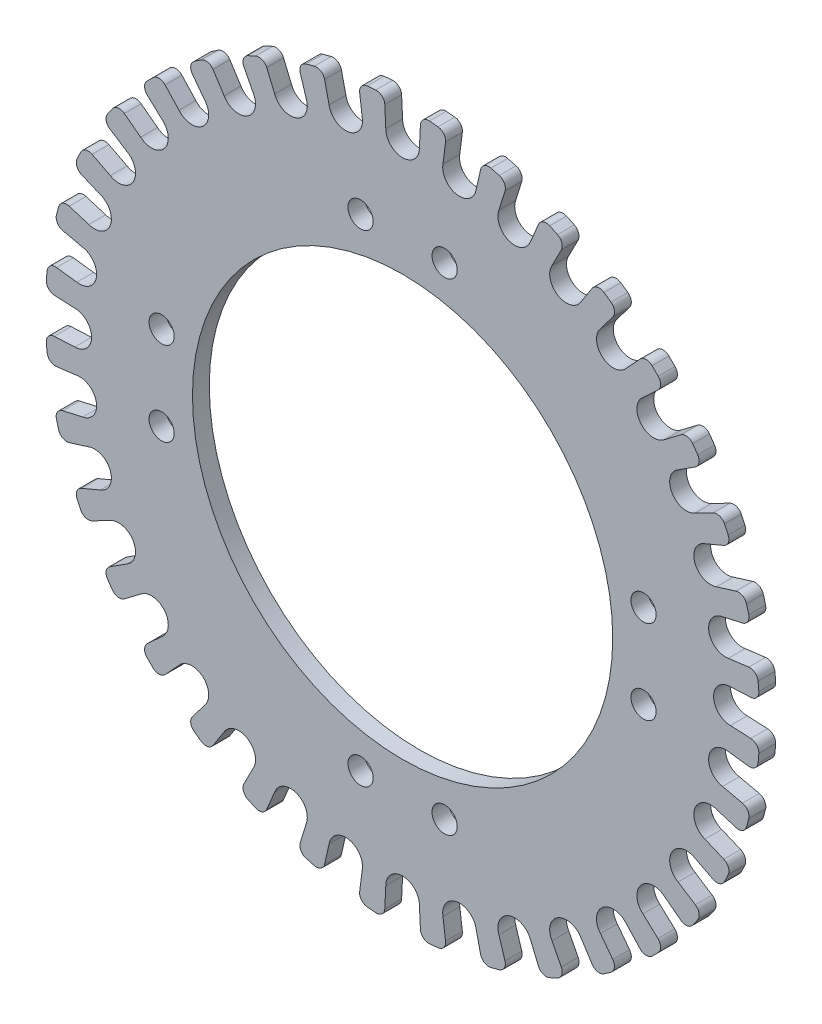
SolidWorks part; units mm, degrees
ref_plane "Front Plane" through (0, 0, 0) normal (0, 0, 1) x (1, 0, 0)
ref_plane "Top Plane" through (0, 0, 0) normal (0, 1, 0) x (1, 0, 0)
ref_plane "Right Plane" through (0, 0, 0) normal (1, 0, 0) x (0, 0, -1)
sketch "Sketch1" plane through (0, 0, 0) normal (0, 0, 1) x (1, 0, 0)
  line L0 (0, 0) -> (0, 76.7228) construction
  line L1 (-5, 28.6654) -> (7.5438, 28.6654) construction
  line L2 (-1.65, 27.0934) -> (1.65, 27.0934) construction
  line L3 (-1.65, 27.0934) -> (-1.65, 38.3614) construction
  line L4 (-1.65, 38.3614) -> (1.65, 38.3614) construction
  line L5 (1.65, 27.0934) -> (1.65, 38.3614) construction
  circle A0 centre (0, 0) radius 42.5
  circle A1 centre (0, 0) radius 25
  circle A2 centre (-5, 28.6654) radius 1.5
  circle A3 centre (5, 28.6654) radius 1.5
  circle A4 centre (28.6654, 5) radius 1.5
  circle A5 centre (28.6654, -5) radius 1.5
  circle A6 centre (5, -28.6654) radius 1.5
  circle A7 centre (-5, -28.6654) radius 1.5
  circle A8 centre (-28.6654, -5) radius 1.5
  circle A9 centre (-28.6654, 5) radius 1.5
  point P7 (0, 42.5)
  point P10 (0, 38.3614)
  dimension "D1" = 85
  dimension "D2" = 50
  dimension "D3" = 3
  dimension "D4" = 3.3
  dimension "D5" = 5
  dimension "D6" = 4
extrude "Boss-Extrude1" add sketch "Sketch1" along normal blind 2
sketch "Sketch2" plane through (0, 0, 2) normal (0, 0, 1) x (1, 0, 0)
  line L0 (0, 0) -> (0, 46.0615) construction
  line L1 (-2, 39) -> (-2.25, 44.1517)
  line L2 (-2.25, 44.1517) -> (2.25, 44.1517)
  line L3 (2.25, 44.1517) -> (2, 39)
  arc A0 (-2, 39) -> (2, 39) centre (0, 39) ccw
  circle A1 centre (0, 0) radius 42.5 construction
  point P4 (0, 44.1517)
  point P5 (0, 42.5)
  dimension "D1" = 3.5
  dimension "D3" = 2.25
  dimension "D2" = 2
extrude "Cut-Extrude1" cut sketch "Sketch2" against normal through all
sketch "Sketch5" plane through (0, 0, 2) normal (0, 0, 1) x (1, 0, 0)
  line L0 (3.8898, 40.5) -> (-1.3229, 40.5) construction
  line L1 (0, 42.5) -> (3.8939, 42.5) construction
  line L4 (-2, 39) -> (-2.1672, 42.4447)
  line L5 (-2, 39) -> (-2.1672, 42.4447)
  line L6 (2.1672, 42.4447) -> (2, 39)
  line L7 (2.1672, 42.4447) -> (2, 39)
  circle A0 centre (0, 39) radius 2 construction
  circle A1 centre (0, 0) radius 42.5 construction
  arc A3 (-2.1672, 42.4447) -> (2.1672, 42.4447) centre (0, 0) ccw
  arc A4 (-2.1672, 42.4447) -> (2.1672, 42.4447) centre (0, 0) ccw
  arc A194 (-2, 39) -> (2, 39) centre (0, 39) ccw
  arc A195 (-2, 39) -> (2, 39) centre (0, 39) ccw
  dimension "D1" = 0
  dimension "D2" = 2
fillet "Fillet1" radius 1 2 edges at (-2.1672, 42.4447, 1) (2.1672, 42.4447, 1)
pattern_circular "CirPattern1" count 36 over 360 about axis through (0, 0, 0) along (0, 0, 1) of "Fillet1", "Cut-Extrude1"
